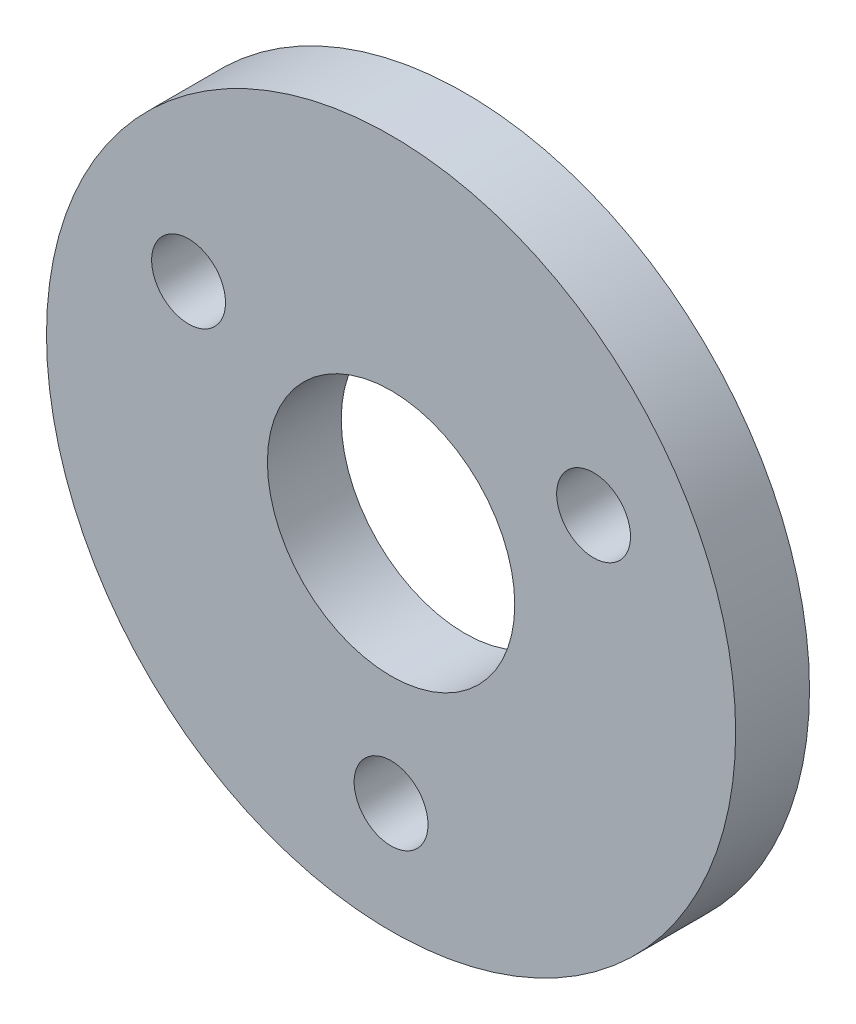
SolidWorks part; units mm, degrees
ref_plane "前视基准面" through (0, 0, 0) normal (0, 0, 1) x (1, 0, 0)
ref_plane "上视基准面" through (0, 0, 0) normal (0, 1, 0) x (1, 0, 0)
ref_plane "右视基准面" through (0, 0, 0) normal (1, 0, 0) x (0, 0, -1)
sketch "草图1" plane through (0, 0, 0) normal (0, 0, 1) x (1, 0, 0)
  circle A0 centre (0, 0) radius 14
  circle A1 centre (0, 0) radius 5.025
  circle A2 centre (0, -9.5) radius 1.5
  circle A3 centre (-8.2272, 4.75) radius 1.5
  circle A4 centre (8.2272, 4.75) radius 1.5
  dimension "D1" = 28
  dimension "D2" = 10.05
  dimension "D3" = 9.5
  dimension "D4" = 3
  dimension "D5" = 3
extrude "凸台-拉伸1" add sketch "草图1" along normal blind 3
